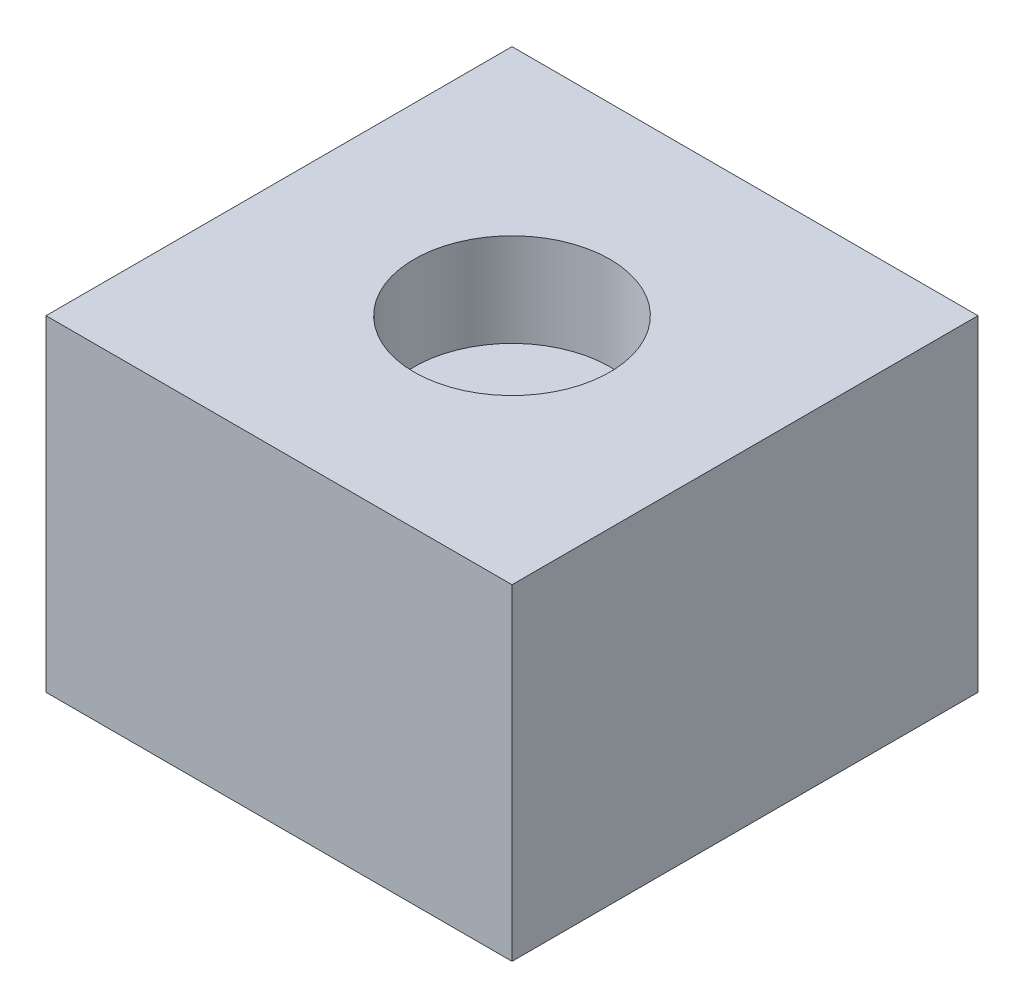
SolidWorks part; units mm, degrees
ref_plane "Front Plane" through (0, 0, 0) normal (0, 0, 1) x (1, 0, 0)
ref_plane "Top Plane" through (0, 0, 0) normal (0, 1, 0) x (1, 0, 0)
ref_plane "Right Plane" through (0, 0, 0) normal (1, 0, 0) x (0, 0, -1)
sketch "Sketch1" plane through (0, 0, 0) normal (0, 1, 0) x (1, 0, 0)
  line L1 (0, 0) -> (10, 0)
  line L2 (0, 0) -> (0, 10)
  line L3 (0, 10) -> (10, 10)
  line L4 (10, 0) -> (10, 10)
  dimension "D1" = 10
  dimension "D2" = 10
extrude "Boss-Extrude1" add sketch "Sketch1" along normal blind 7
sketch "Sketch2" plane through (0, 7, 0) normal (0, 1, 0) x (1, 0, 0)
  line L0 (0, 10) -> (10, 0) construction
  line L1 (10, 10) -> (0, 0) construction
  circle A0 centre (5, 5) radius 2.1
  dimension "D1" = 4.2
extrude "Cut-Extrude1" cut sketch "Sketch2" against normal blind 2
